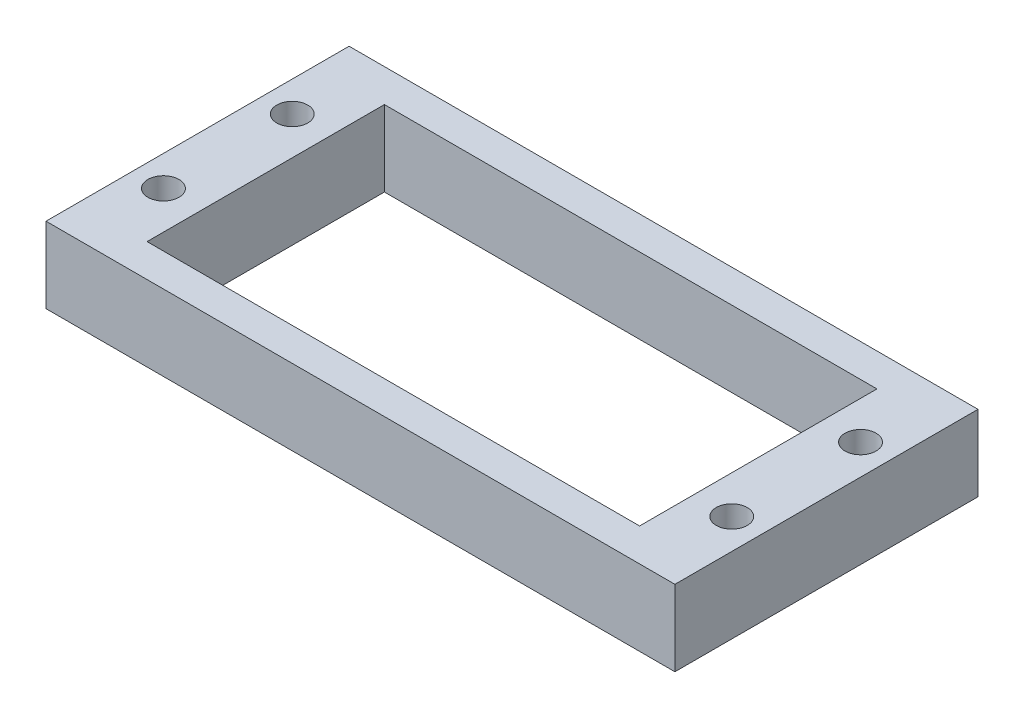
SolidWorks part; units mm, degrees
ref_plane "Front Plane" through (0, 0, 0) normal (0, 0, 1) x (1, 0, 0)
ref_plane "Top Plane" through (0, 0, 0) normal (0, 1, 0) x (1, 0, 0)
ref_plane "Right Plane" through (0, 0, 0) normal (1, 0, 0) x (0, 0, -1)
sketch "Sketch1" plane through (0, 0, 0) normal (0, 1, 0) x (1, 0, 0)
  line L0 (-41.5, 0) -> (41.5, 0) construction
  line L1 (-41.5, 20) -> (41.5, 20)
  line L2 (-41.5, 20) -> (-41.5, -20)
  line L3 (-41.5, -20) -> (41.5, -20)
  line L4 (41.5, 20) -> (41.5, -20)
  line L5 (-41.5, 20) -> (41.5, -20) construction
  line L6 (-41.5, -20) -> (41.5, 20) construction
  line L7 (-32.5, 15.6627) -> (32.5, 15.6627)
  line L8 (-32.5, 15.6627) -> (-32.5, -15.6627)
  line L9 (-32.5, -15.6627) -> (32.5, -15.6627)
  line L10 (32.5, 15.6627) -> (32.5, -15.6627)
  line L11 (-32.5, 15.6627) -> (32.5, -15.6627) construction
  line L12 (-32.5, -15.6627) -> (32.5, 15.6627) construction
  line L13 (-37.5, 8.5) -> (-37.5, -8.5)
  line L14 (0, 20) -> (0, -20) construction
  circle A0 centre (-37.5, 8.5) radius 2.05
  circle A1 centre (-37.5, -8.5) radius 2.05
  circle A2 centre (37.5, -8.5) radius 2.05
  circle A3 centre (37.5, 8.5) radius 2.05
  point P0 (0, 0)
  point P6 (0, 0)
  point P16 (-37.5, 0)
  dimension "D6" = 4.1
  dimension "D1" = 83
  dimension "D2" = 40
  dimension "D3" = 65
  dimension "D4" = 31.3253
  dimension "D5" = 17
  dimension "D7" = 37.5
extrude "Boss-Extrude1" add sketch "Sketch1" along normal blind 10
